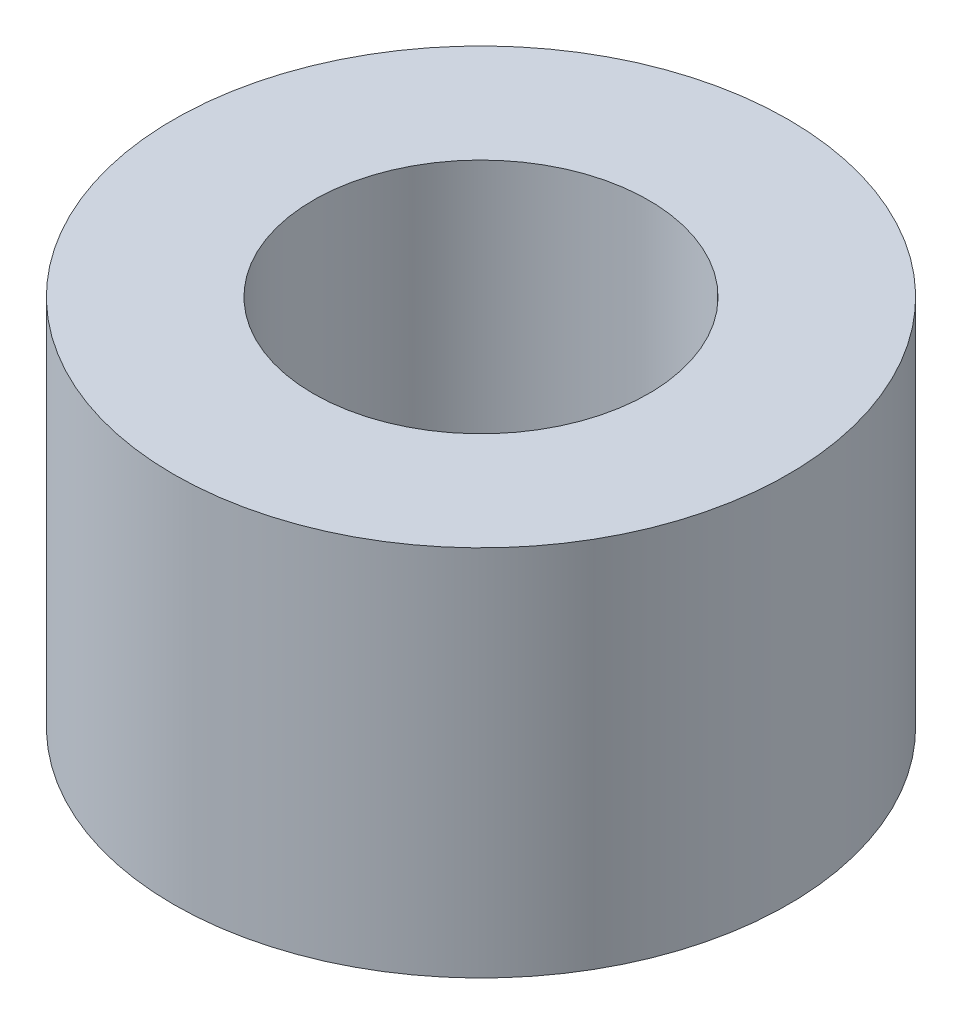
SolidWorks part; units mm, degrees
ref_plane "Front Plane" through (0, 0, 0) normal (0, 0, 1) x (1, 0, 0)
ref_plane "Top Plane" through (0, 0, 0) normal (0, 1, 0) x (1, 0, 0)
ref_plane "Right Plane" through (0, 0, 0) normal (1, 0, 0) x (0, 0, -1)
sketch "Sketch1" plane through (0, 0, 0) normal (0, 1, 0) x (1, 0, 0)
  circle A0 centre (0, 0) radius 1.8
  circle A1 centre (0, 0) radius 3.3
  dimension "D1" = 3.6
  dimension "D2" = 1.5
extrude "Boss-Extrude1" add sketch "Sketch1" along normal blind 4
